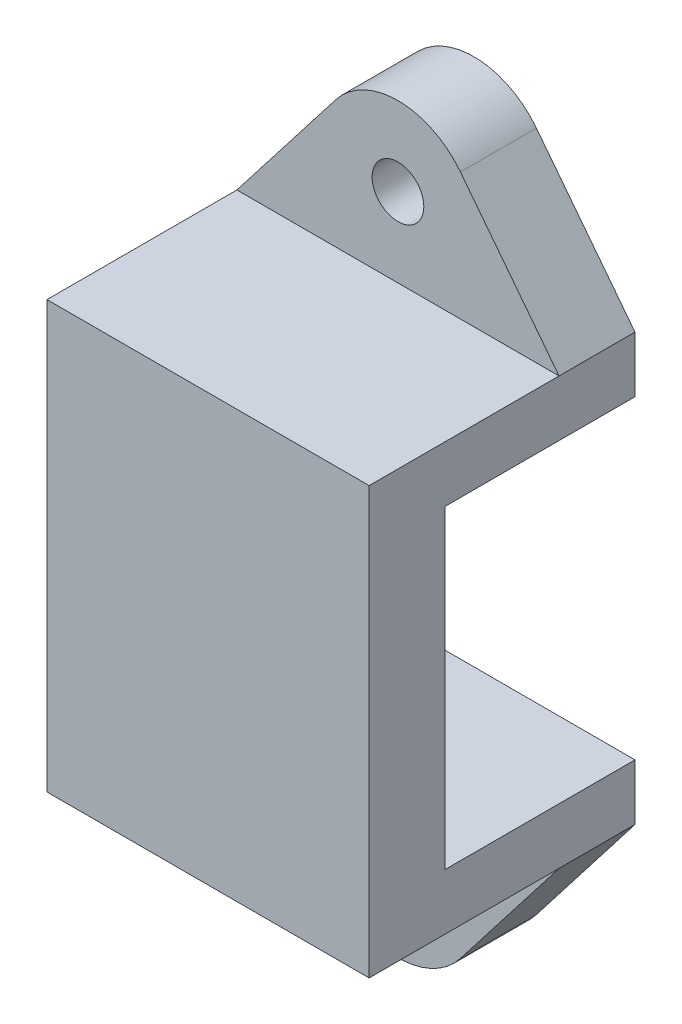
SolidWorks part; units mm, degrees
ref_plane "Front Plane" through (0, 0, 0) normal (0, 0, 1) x (1, 0, 0)
ref_plane "Top Plane" through (0, 0, 0) normal (0, 1, 0) x (1, 0, 0)
ref_plane "Right Plane" through (0, 0, 0) normal (1, 0, 0) x (0, 0, -1)
sketch "Sketch5" plane through (0, 0, 0) normal (0, 0, 1) x (1, 0, 0)
  line L0 (1, 36.1467) -> (7.4924, 44.5293)
  line L2 (5.55, 22.1123) -> (8.9535, 22.1123)
  line L3 (22.2056, 36.1467) -> (15.7132, 44.5293)
  line L4 (22.2056, 36.1467) -> (22.2056, 32.4623)
  line L6 (22.2056, 32.4623) -> (1, 32.4623)
  line L8 (1, 32.4623) -> (1, 36.1467)
  line L10 (1, 11.7623) -> (1, 8.078)
  line L11 (22.2056, 11.7623) -> (1, 11.7623)
  line L12 (22.2056, 8.078) -> (22.2056, 11.7623)
  line L13 (22.2056, 8.078) -> (15.7132, -0.3046)
  line L14 (1, 8.078) -> (7.4924, -0.3046)
  circle A0 centre (11.6028, 41.3457) radius 1.7
  arc A1 (15.7132, 44.5293) -> (7.4924, 44.5293) centre (11.6028, 41.3457) ccw
  arc A2 (15.7132, -0.3046) -> (7.4924, -0.3046) centre (11.6028, 2.879) cw
  circle A3 centre (11.6028, 2.879) radius 1.7
  line M16 (22.2056, 36.1467) -> (15.7132, 44.5293)
  arc M17 (15.7132, 44.5293) -> (7.4924, 44.5293) centre (11.6028, 41.3457) ccw
  line M18 (7.4924, 44.5293) -> (1, 36.1467)
  line M19 (1, 36.1467) -> (1, 31)
  line M26 (5.2, 32.4623) -> (46.35, 32.4623)
  line M28 (46.35, 11.7623) -> (5.2, 11.7623)
  circle M38 centre (11.6028, 41.3457) radius 1.7
  circle M39 centre (11.6028, 2.879) radius 1.7
extrude "Boss-Extrude5" add sketch "Sketch5" along normal blind 5 contours L6 L4 M26 M16 M17 M18 M19 M38 | A2 L13 L12 L11 L10 L14 M28 M39
sketch "Sketch6" plane through (0, 0, 5) normal (0, 0, 1) x (1, 0, 0)
  line L0 (1, 11.7623) -> (1, 8.078)
  line L1 (1, 8.078) -> (22.2056, 8.078)
  line L2 (22.2056, 8.078) -> (22.2056, 11.7623)
  line L3 (22.2056, 11.7623) -> (1, 11.7623)
  line L4 (1, 36.1467) -> (1, 32.4623)
  line L5 (1, 36.1467) -> (1, 31) construction
  line L6 (1, 36.1467) -> (1, 32.4623) construction
  line L7 (1, 32.4623) -> (22.2056, 32.4623)
  line L8 (22.2056, 32.4623) -> (22.2056, 36.1467)
  line L9 (22.2056, 36.1467) -> (1, 36.1467)
extrude "Boss-Extrude6" add sketch "Sketch6" along normal offset from surface (7.5 mm away) 0.2
sketch "Sketch7" plane through (0, 0, 12.5) normal (0, 0, 1) x (1, 0, 0)
  line L1 (1, 36.1467) -> (22.2056, 36.1467)
  line L2 (1, 36.1467) -> (1, 8.078)
  line L3 (1, 8.078) -> (22.2056, 8.078)
  line L4 (22.2056, 36.1467) -> (22.2056, 8.078)
extrude "Boss-Extrude7" add sketch "Sketch7" along normal blind 5
